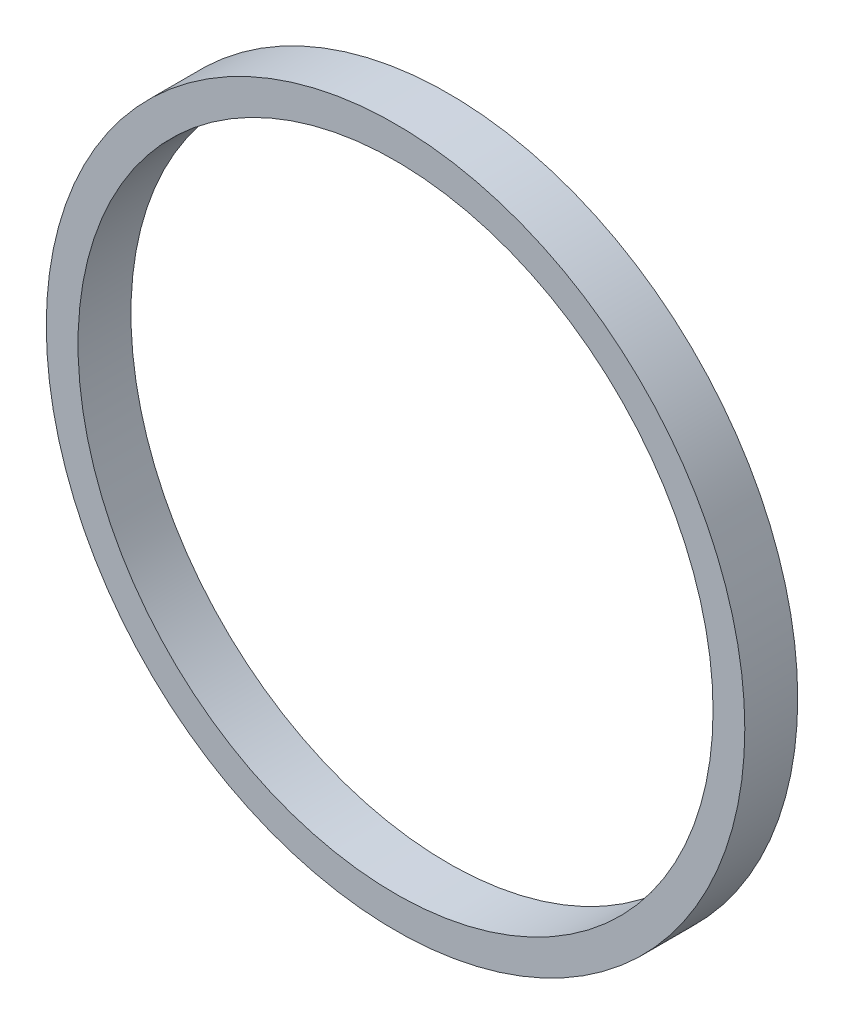
SolidWorks part; units mm, degrees
ref_plane "Front Plane" through (0, 0, 0) normal (0, 0, 1) x (1, 0, 0)
ref_plane "Top Plane" through (0, 0, 0) normal (0, 1, 0) x (1, 0, 0)
ref_plane "Right Plane" through (0, 0, 0) normal (1, 0, 0) x (0, 0, -1)
sketch "Sketch1" plane through (0, 0, 0) normal (0, 0, 1) x (1, 0, 0)
  line L0 (55, 0) -> (-55, 0) construction
  circle A0 centre (-0.746, 0) radius 33
  circle A1 centre (-0.746, 0) radius 30
  dimension "D1" = 66
  dimension "D2" = 3
extrude "Boss-Extrude1" add sketch "Sketch1" along normal blind 5
